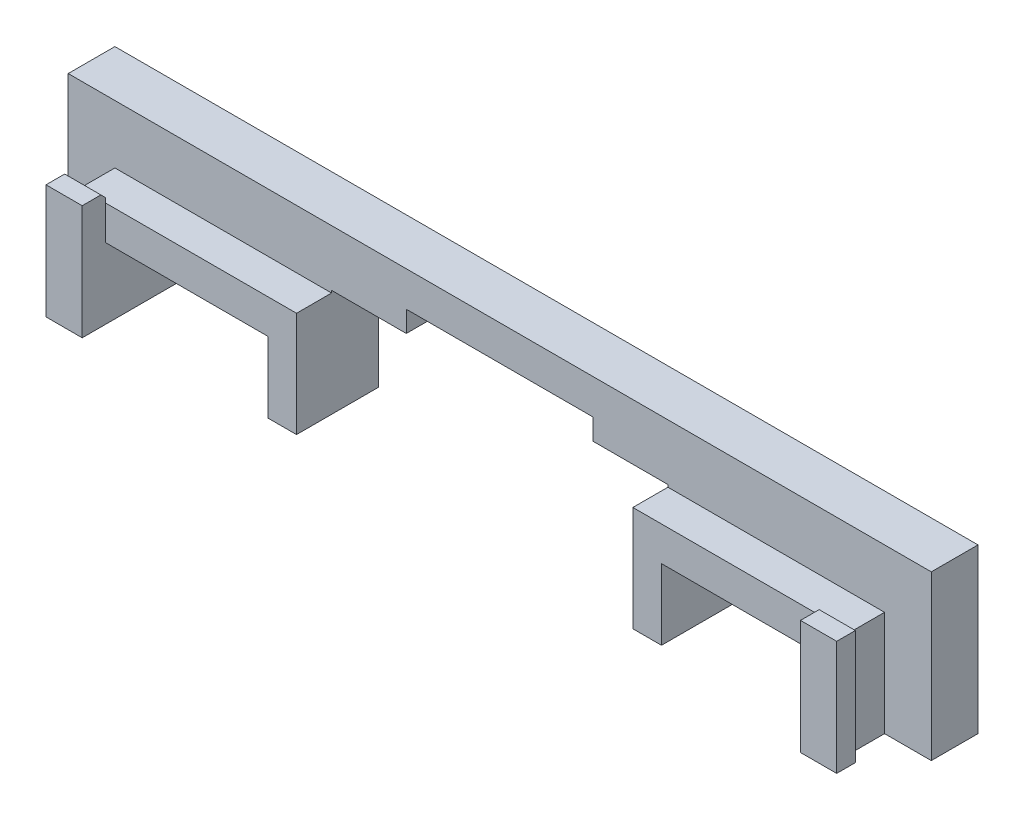
SolidWorks part; units mm, degrees
ref_plane "Front Plane" through (0, 0, 0) normal (0, 0, 1) x (1, 0, 0)
ref_plane "Top Plane" through (0, 0, 0) normal (0, 1, 0) x (1, 0, 0)
ref_plane "Right Plane" through (0, 0, 0) normal (1, 0, 0) x (0, 0, -1)
sketch "Sketch2" plane through (0, 0, 0) normal (0, 0, 1) x (1, 0, 0)
  line L0 (281.4314, 89.4547) -> (281.4314, 94.4547) construction
  line L1 (288.4314, 89.4547) -> (274.4314, 89.4547) construction
  line L2 (285.4314, 90.4547) -> (277.4314, 90.4547)
  line L3 (277.4314, 90.4547) -> (277.4314, 89.5547)
  line L4 (277.4314, 89.5547) -> (274.2314, 89.5547)
  line L5 (274.2314, 89.5547) -> (274.2314, 84.9556)
  line L6 (274.2314, 84.9556) -> (273.0063, 84.9556)
  line L7 (273.0063, 84.9556) -> (273.0063, 87.9858)
  line L8 (273.0063, 87.9858) -> (266.0559, 87.9858)
  line L9 (266.0559, 87.9858) -> (266.0559, 84.9556)
  line L10 (266.0559, 84.9556) -> (264.9558, 84.9556)
  line L11 (264.9558, 84.9556) -> (264.9558, 91.9547)
  line L12 (264.9558, 91.9547) -> (297.907, 91.9547)
  line L13 (274.4314, 89.4547) -> (274.4314, 84.7556) construction
  line L14 (274.4314, 84.7556) -> (272.9063, 84.7556) construction
  line L15 (272.9063, 84.7556) -> (272.9063, 87.9858) construction
  line L16 (264.9058, 89.4547) -> (264.9058, 75.4547) construction
  line L17 (266.1559, 84.7556) -> (265.3309, 84.7556) construction
  line L18 (266.1559, 87.9858) -> (266.1559, 84.7556) construction
  line L19 (272.9063, 87.9858) -> (266.1559, 87.9858) construction
  line L20 (297.907, 84.9556) -> (297.907, 91.9547)
  line L21 (296.8069, 84.9556) -> (297.907, 84.9556)
  line L22 (296.8069, 87.9858) -> (296.8069, 84.9556)
  line L23 (289.8565, 87.9858) -> (296.8069, 87.9858)
  line L24 (289.8565, 84.9556) -> (289.8565, 87.9858)
  line L25 (288.6314, 84.9556) -> (289.8565, 84.9556)
  line L26 (288.6314, 89.5547) -> (288.6314, 84.9556)
  line L27 (285.4314, 89.5547) -> (288.6314, 89.5547)
  line L28 (285.4314, 90.4547) -> (285.4314, 89.5547)
  point P26 (265.7434, 84.7556)
  point P34 (281.4314, 91.9547)
  point P43 (281.4314, 90.4547)
  dimension "D1" = 0.2
  dimension "D2" = 0.2
  dimension "D3" = 0.1
  dimension "D4" = 0.05
  dimension "D5" = 0.2
  dimension "D6" = 0.1
  dimension "D7" = 0
  dimension "D8" = 0.1
  dimension "D9" = 1
  dimension "D10" = 3
  dimension "D11" = 1.5
extrude "Boss-Extrude1" add sketch "Sketch2" against normal blind 2
sketch "Sketch3" plane through (0, 0, 0) normal (0, 0, 1) x (1, 0, 0)
  line L0 (264.9558, 89.4547) -> (297.907, 89.4547)
  line L1 (264.9058, 89.4547) -> (297.957, 89.4547) construction
  line L20 (277.4314, 89.5547) -> (277.4314, 90.4547)
  line L21 (277.4314, 90.4547) -> (285.4314, 90.4547)
  line L22 (285.4314, 90.4547) -> (285.4314, 89.5547)
  line L23 (285.4314, 89.5547) -> (288.6314, 89.5547)
  line L24 (288.6314, 89.5547) -> (288.6314, 84.9556)
  line L25 (288.6314, 84.9556) -> (289.8565, 84.9556)
  line L26 (289.8565, 84.9556) -> (289.8565, 87.9858)
  line L27 (289.8565, 87.9858) -> (296.8069, 87.9858)
  line L28 (296.8069, 87.9858) -> (296.8069, 84.9556)
  line L29 (296.8069, 84.9556) -> (297.907, 84.9556)
  line L30 (297.907, 84.9556) -> (297.907, 91.9547)
  line L31 (297.907, 91.9547) -> (264.9558, 91.9547)
  line L32 (264.9558, 91.9547) -> (264.9558, 84.9556)
  line L33 (264.9558, 84.9556) -> (266.0559, 84.9556)
  line L34 (266.0559, 84.9556) -> (266.0559, 87.9858)
  line L35 (266.0559, 87.9858) -> (273.0063, 87.9858)
  line L36 (273.0063, 87.9858) -> (273.0063, 84.9556)
  line L37 (273.0063, 84.9556) -> (274.2314, 84.9556)
  line L38 (274.2314, 84.9556) -> (274.2314, 89.5547)
  line L39 (274.2314, 89.5547) -> (277.4314, 89.5547)
  line L40 (277.4314, 89.5547) -> (277.4314, 90.4547)
  line L41 (277.4314, 90.4547) -> (285.4314, 90.4547)
  line L42 (285.4314, 90.4547) -> (285.4314, 89.5547)
  line L43 (285.4314, 89.5547) -> (288.6314, 89.5547)
  line L44 (288.6314, 89.5547) -> (288.6314, 84.9556)
  line L45 (288.6314, 84.9556) -> (289.8565, 84.9556)
  line L46 (289.8565, 84.9556) -> (289.8565, 87.9858)
  line L47 (289.8565, 87.9858) -> (296.8069, 87.9858)
  line L48 (296.8069, 87.9858) -> (296.8069, 84.9556)
  line L49 (296.8069, 84.9556) -> (297.907, 84.9556)
  line L50 (297.907, 84.9556) -> (297.907, 91.9547)
  line L51 (297.907, 91.9547) -> (264.9558, 91.9547)
  line L52 (264.9558, 91.9547) -> (264.9558, 84.9556)
  line L53 (264.9558, 84.9556) -> (266.0559, 84.9556)
  line L54 (266.0559, 84.9556) -> (266.0559, 87.9858)
  line L55 (266.0559, 87.9858) -> (273.0063, 87.9858)
  line L56 (273.0063, 87.9858) -> (273.0063, 84.9556)
  line L57 (273.0063, 84.9556) -> (274.2314, 84.9556)
  line L58 (274.2314, 84.9556) -> (274.2314, 89.5547)
  line L59 (274.2314, 89.5547) -> (277.4314, 89.5547)
  line M26 (288.6314, 89.5547) -> (288.6314, 84.9556)
  line M27 (288.6314, 84.9556) -> (289.8565, 84.9556)
  line M28 (289.8565, 84.9556) -> (289.8565, 87.9858)
  line M29 (289.8565, 87.9858) -> (296.8069, 87.9858)
  line M30 (296.8069, 87.9858) -> (296.8069, 84.9556)
  line M31 (296.8069, 84.9556) -> (297.907, 84.9556)
  line M32 (297.907, 84.9556) -> (297.907, 91.9547)
  line M34 (264.9558, 91.9547) -> (264.9558, 84.9556)
  line M35 (264.9558, 84.9556) -> (266.0559, 84.9556)
  line M36 (266.0559, 84.9556) -> (266.0559, 87.9858)
  line M37 (266.0559, 87.9858) -> (273.0063, 87.9858)
  line M38 (273.0063, 87.9858) -> (273.0063, 84.9556)
  line M39 (273.0063, 84.9556) -> (274.2314, 84.9556)
  line M40 (274.2314, 84.9556) -> (274.2314, 89.5547)
  dimension "D2" = 0
  dimension "D1" = 0
extrude "Boss-Extrude2" add sketch "Sketch3" along normal blind 1.5 contours L0 M34 M35 M36 M37 M38 M39 M40 | L0 M26 M27 M28 M29 M30 M31 M32
sketch "Sketch4" plane through (0, 0, 1.5) normal (0, 0, 1) x (1, 0, 0)
  line L0 (281.4314, 89.4547) -> (281.4314, 96.1398) construction
  line L1 (288.4314, 89.4547) -> (274.4314, 89.4547) construction
  line L3 (264.5058, 89.8547) -> (266.0559, 89.8547)
  line L4 (264.5058, 89.8547) -> (264.5058, 84.9556)
  line L5 (264.5058, 84.9556) -> (266.0559, 84.9556)
  line L6 (266.0559, 89.8547) -> (266.0559, 84.9556)
  line L8 (298.357, 84.9556) -> (296.8069, 84.9556)
  line L9 (296.8069, 89.8547) -> (296.8069, 84.9556)
  line L10 (298.357, 89.8547) -> (296.8069, 89.8547)
  line L11 (298.357, 89.8547) -> (298.357, 84.9556)
  line L13 (264.9058, 89.4547) -> (264.9058, 75.4547) construction
  line L14 (264.9058, 89.4547) -> (297.957, 89.4547) construction
  point P8 (264.0126, 88.8811)
  point P9 (265.9559, 88.1858)
  point P21 (0, 0)
  point P22 (266.0559, 84.9556)
  dimension "D1" = 0.4
  dimension "D2" = 0.4
extrude "Boss-Extrude3" add sketch "Sketch4" along normal blind 1
chamfer "Chamfer1" distance 0.2 angle 45 4 edges at (297.582, 89.8547, 1.5) (265.2809, 89.8547, 1.5) (298.357, 87.4052, 1.5) (264.5058, 87.4052, 1.5)
sketch "Sketch5" plane through (0, 0, -2) normal (0, 0, -1) x (-1, 0, 0)
  line L0 (-266.0559, 87.9858) -> (-273.0063, 87.9858) construction
  line L1 (-267.88, 87.9858) -> (-271.1802, 87.9858)
  line L2 (-267.88, 87.9858) -> (-267.88, 88.9858)
  line L3 (-267.88, 88.9858) -> (-271.1802, 88.9858)
  line L4 (-271.1802, 87.9858) -> (-271.1802, 88.9858)
  line L5 (-267.88, 75.6847) -> (-267.88, 74.4846) construction
  line L6 (-271.1802, 74.4846) -> (-271.1802, 75.6847) construction
  line L8 (-281.4314, 89.4547) -> (-281.4314, 96.8892) construction
  line L9 (-288.4314, 89.4547) -> (-274.4314, 89.4547) construction
  line L10 (-294.9828, 88.9858) -> (-291.6826, 88.9858)
  line L11 (-291.6826, 87.9858) -> (-291.6826, 88.9858)
  line L12 (-294.9828, 87.9858) -> (-291.6826, 87.9858)
  line L13 (-294.9828, 87.9858) -> (-294.9828, 88.9858)
  dimension "D1" = 1
extrude "Cut-Extrude1" cut sketch "Sketch5" against normal up to surface (2 mm away)
sketch "Sketch6" plane through (0, 0, -2) normal (0, 0, -1) x (-1, 0, 0)
  line L0 (-297.907, 91.9547) -> (-264.9558, 91.9547) construction
  line L1 (-297.907, 84.9556) -> (-299.907, 84.9556)
  line L2 (-297.907, 84.9556) -> (-297.907, 91.9547)
  line L3 (-297.907, 91.9547) -> (-299.907, 91.9547)
  line L4 (-299.907, 84.9556) -> (-299.907, 91.9547)
  line L6 (-264.9558, 91.9547) -> (-262.9558, 91.9547)
  line L7 (-264.9558, 91.9547) -> (-264.9558, 84.9556)
  line L8 (-264.9558, 84.9556) -> (-262.9558, 84.9556)
  line L9 (-262.9558, 91.9547) -> (-262.9558, 84.9556)
  dimension "D1" = 2
extrude "Boss-Extrude4" add sketch "Sketch6" against normal up to surface (2 mm away)
